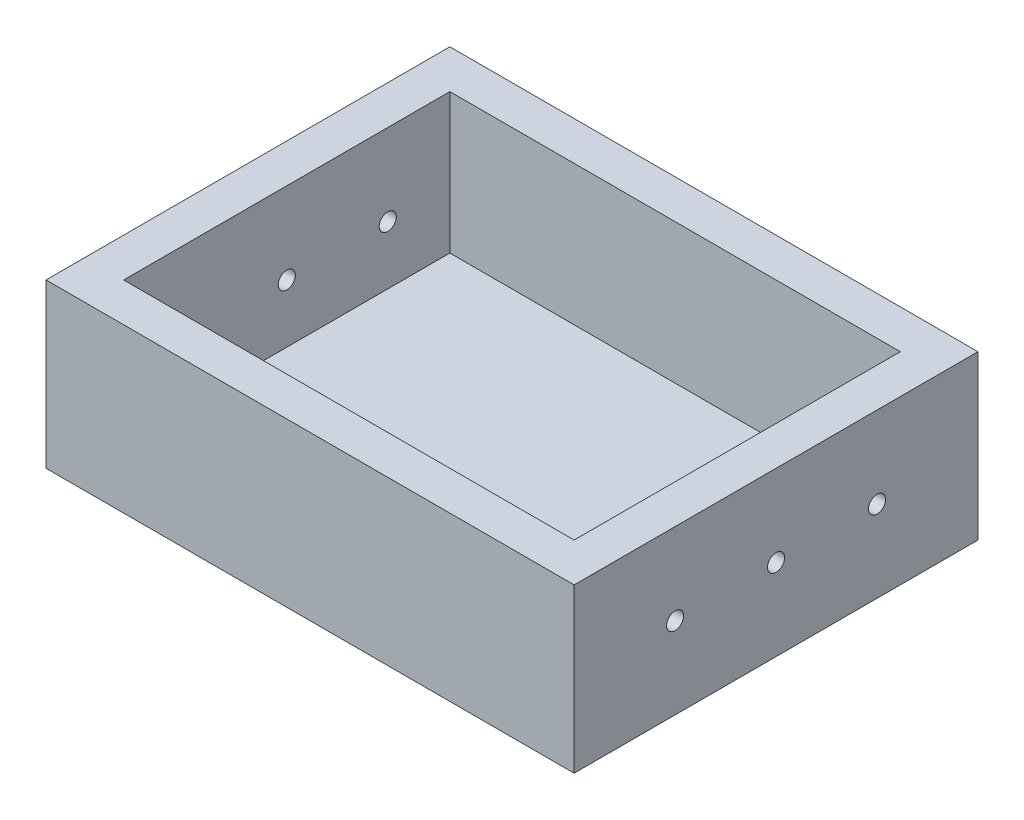
SolidWorks part; units mm, degrees
ref_plane "前视基准面" through (0, 0, 0) normal (0, 0, 1) x (1, 0, 0)
ref_plane "上视基准面" through (0, 0, 0) normal (0, 1, 0) x (1, 0, 0)
ref_plane "右视基准面" through (0, 0, 0) normal (1, 0, 0) x (0, 0, -1)
sketch "草图1" plane through (0, 0, 0) normal (0, 1, 0) x (1, 0, 0)
  line L1 (-68, 52) -> (68, 52)
  line L2 (-68, 52) -> (-68, -52)
  line L3 (-68, -52) -> (68, -52)
  line L4 (68, 52) -> (68, -52)
  line L5 (-68, 52) -> (68, -52) construction
  line L6 (-68, -52) -> (68, 52) construction
  point P0 (0, 0)
  dimension "D1" = 136
  dimension "D2" = 104
extrude "凸台-拉伸1" add sketch "草图1" along normal blind 42
sketch "草图2" plane through (0, 42, 0) normal (0, 1, 0) x (1, 0, 0)
  line L1 (-58, 42) -> (58, 42)
  line L2 (-58, 42) -> (-58, -42)
  line L3 (-58, -42) -> (58, -42)
  line L4 (58, 42) -> (58, -42)
  line L5 (-58, 42) -> (58, -42) construction
  line L6 (-58, -42) -> (58, 42) construction
  point P0 (0, 0)
  dimension "D1" = 116
  dimension "D2" = 84
extrude "切除-拉伸1" cut sketch "草图2" against normal blind 36
sketch "草图6" plane through (-68, 0, 0) normal (-1, 0, 0) x (0, 0, 1)
  line L0 (-52, 21) -> (52, 21) construction
  line L1 (-52, 42) -> (-52, 0) construction
  line L2 (52, 42) -> (52, 0) construction
  line L3 (0, 42) -> (0, 0) construction
  line L4 (-52, 42) -> (52, 42) construction
  circle A0 centre (-26, 21) radius 2.2
  circle A1 centre (26, 21) radius 2.2
  circle A2 centre (0, 21) radius 2.2
  dimension "D1" = 4.4
  dimension "D2" = 4.4
  dimension "D5" = 4.4
  dimension "D3" = 26
  dimension "D4" = 26
extrude "切除-拉伸5" cut sketch "草图6" against normal blind 136
